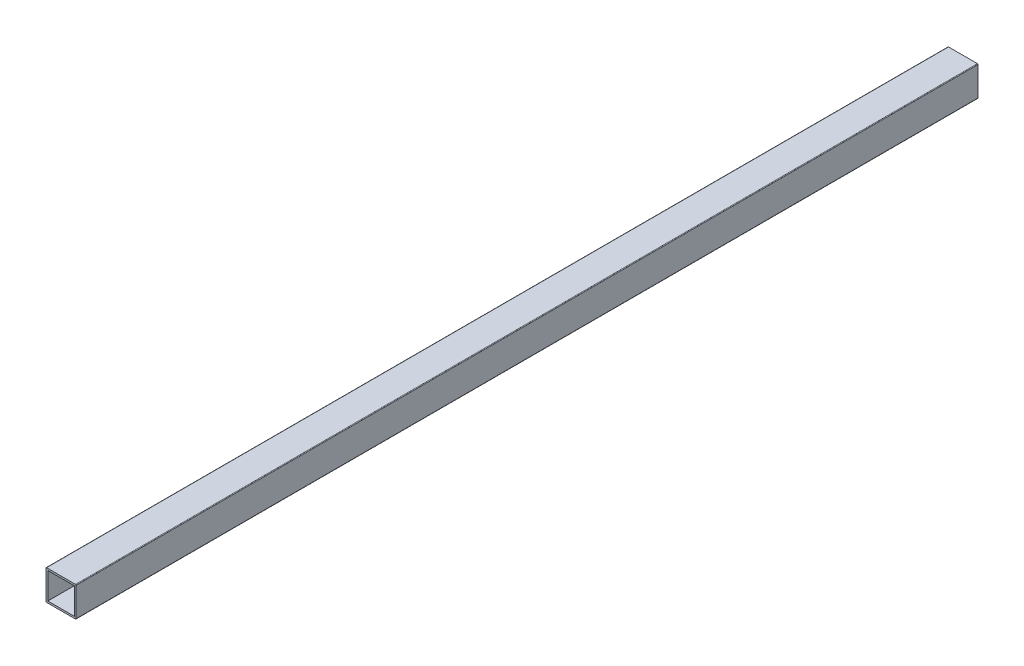
SolidWorks part; units mm, degrees
material "ASTM A36 Aço"
ref_plane "Plano frontal" through (0, 0, 0) normal (0, 0, 1) x (1, 0, 0)
ref_plane "Plano superior" through (0, 0, 0) normal (0, 1, 0) x (1, 0, 0)
ref_plane "Plano direito" through (0, 0, 0) normal (1, 0, 0) x (0, 0, -1)
sketch "Esboço1" plane through (0, 0, 0) normal (0, 0, 1) x (1, 0, 0)
  line L0 (22, 22) -> (-22, 22)
  line L1 (24, 25) -> (-24, 25)
  line L2 (25, 24) -> (25, -24)
  line L3 (24, -25) -> (-24, -25)
  line L4 (-25, 24) -> (-25, -24)
  line L5 (25, 25) -> (-25, -25) construction
  line L6 (25, -25) -> (-25, 25) construction
  line L7 (-22, 22) -> (-22, -22)
  line L8 (22, -22) -> (-22, -22)
  line L9 (22, 22) -> (22, -22)
  arc A0 (24, 25) -> (25, 24) centre (24, 24) cw
  arc A1 (-25, 24) -> (-24, 25) centre (-24, 24) cw
  arc A2 (-24, -25) -> (-25, -24) centre (-24, -24) cw
  arc A3 (24, -25) -> (25, -24) centre (24, -24) ccw
  arc A4 (-22, 22) -> (-22, 22) centre (-22, 22) cw
  arc A5 (-22, -22) -> (-22, -22) centre (-22, -22) cw
  arc A6 (22, -22) -> (22, -22) centre (22, -22) ccw
  arc A7 (22, 22) -> (22, 22) centre (22, 22) cw
  point P0 (0, 0)
  dimension "D1" = 1
  dimension "D2" = 1
  dimension "D4" = 50
  dimension "D5" = 50
  dimension "D3" = 3
extrude "Ressalto-extrusão1" add sketch "Esboço1" along normal blind 1500
